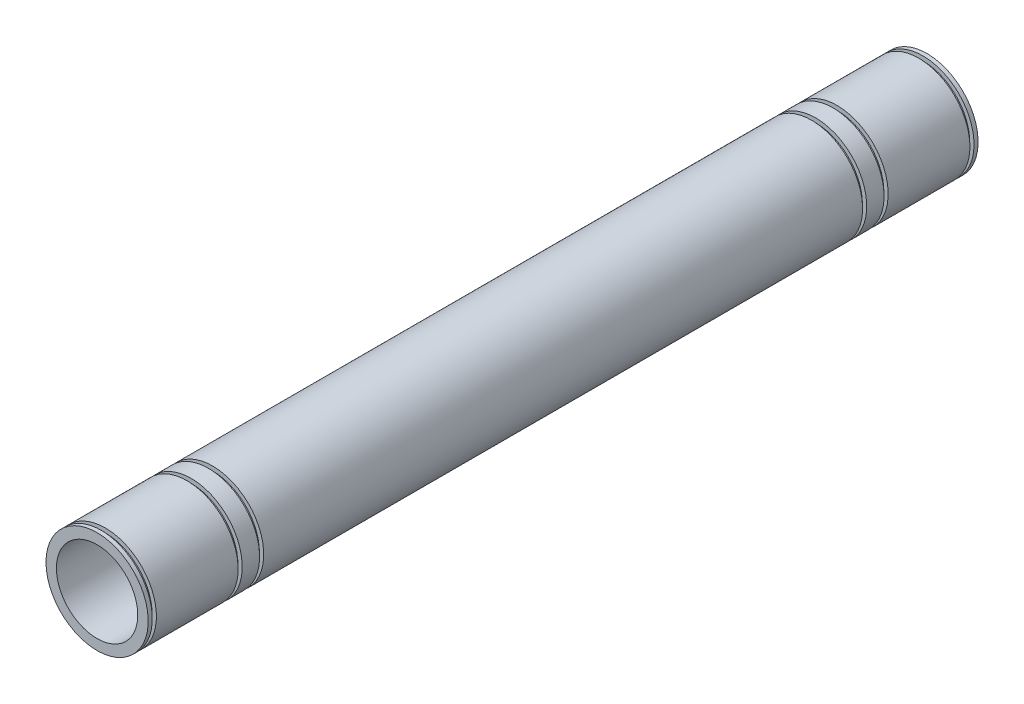
SolidWorks part; units mm, degrees
material "6061-T6 (SS)"
ref_plane "Front Plane" through (0, 0, 0) normal (0, 0, 1) x (1, 0, 0)
ref_plane "Top Plane" through (0, 0, 0) normal (0, 1, 0) x (1, 0, 0)
ref_plane "Right Plane" through (0, 0, 0) normal (1, 0, 0) x (0, 0, -1)
sketch "Sketch1" plane through (0, 0, 0) normal (0, 0, 1) x (1, 0, 0)
  circle A0 centre (0, 0) radius 25
  circle A1 centre (0, 0) radius 19.9
  dimension "D1" = 50
  dimension "D2" = 39.8
extrude "Body" add sketch "Sketch1" along normal blind 406
sketch "Sketch2" plane through (0, 0, 0) normal (1, 0, 0) x (0, 0, -1)
  line L0 (-353, 25) -> (-353, -25) construction
  line L1 (0, 25) -> (-406, 25) construction
  line L2 (-406, -25) -> (0, -25) construction
  line L3 (-406, 25) -> (-406, -25) construction
  line L4 (0, 0) -> (-406, 0) construction
  line L5 (-406, 22.9) -> (0, 22.9) construction
  line L6 (0, -25) -> (0, 25) construction
  line L7 (-203, 25) -> (-203, -25) construction
  line L8 (-404, 25) -> (-402, 25)
  line L9 (-404, 25) -> (-404, 22.9)
  line L10 (-404, 22.9) -> (-402, 22.9)
  line L11 (-402, 25) -> (-402, 22.9)
  line L12 (-362, 25) -> (-360, 25)
  line L13 (-362, 25) -> (-362, 22.9)
  line L14 (-362, 22.9) -> (-360, 22.9)
  line L15 (-360, 25) -> (-360, 22.9)
  line L24 (-56.5, 22.9) -> (-56.5, 25)
  line L25 (-351.5, 22.9) -> (-349.5, 22.9)
  line L26 (-351.5, 22.9) -> (-351.5, 25)
  line L27 (-351.5, 25) -> (-349.5, 25)
  line L28 (-349.5, 22.9) -> (-349.5, 25)
  line L29 (-54.5, 22.9) -> (-56.5, 22.9)
  line L30 (-54.5, 22.9) -> (-54.5, 25)
  line L31 (-54.5, 25) -> (-56.5, 25)
  line L32 (-46, 25) -> (-46, 22.9)
  line L33 (-44, 22.9) -> (-46, 22.9)
  line L34 (-44, 25) -> (-44, 22.9)
  line L35 (-44, 25) -> (-46, 25)
  line L36 (-2, 22.9) -> (-4, 22.9)
  line L37 (-4, 25) -> (-4, 22.9)
  line L38 (-2, 25) -> (-4, 25)
  line L39 (-2, 25) -> (-2, 22.9)
  dimension "D1" = 53
  dimension "D2" = 22.9
  dimension "D3" = 2
  dimension "D4" = 2
  dimension "D5" = 9
  dimension "D6" = 49
  dimension "D7" = 2
  dimension "D8" = 1.5
revolve "Ret Ring Grooves" cut sketch "Sketch2" angle 360 about L4
equation "\"shaft_diameter\"= 50.0mm"
equation "\"ret_ring_inner_diameter\"= 45.8mm"
equation "\"ret_ring_thickness\"= 2.0mm"
equation "\"ret_ring_1_pos\"= 9.0mm"
equation "\"ret_ring_2_pos\"= 49.0mm"
equation "\"ref_length\"= 53.0mm"
equation "\"length\"= 406.0mm"
equation "\"D1@Sketch1\"=\"shaft_diameter\""
equation "\"D2@Sketch1\"=\"shaft_inner_diameter\""
equation "\"D1@Body\" = \"length\""
equation "\"D2@Sketch2\"=\"ret_ring_inner_diameter\"/2"
equation "\"D3@Sketch2\"=\"ret_ring_thickness\""
equation "\"D4@Sketch2\"=\"ret_ring_thickness\""
equation "\"D5@Sketch2\"=\"ret_ring_1_pos\""
equation "\"D6@Sketch2\"=\"ret_ring_2_pos\""
equation "\"shaft_inner_diameter\"= 39.8mm"
equation "\"frame_width\"= 300.0mm"
equation "\"D1@Sketch2\"=(\"length\"-\"frame_width\")/2"
equation "\"D7@Sketch2\"=\"ret_ring_thickness\""
equation "\"frame_wall_thickness\"= 1.5mm"
equation "\"D8@Sketch2\"=\"frame_wall_thickness\""
